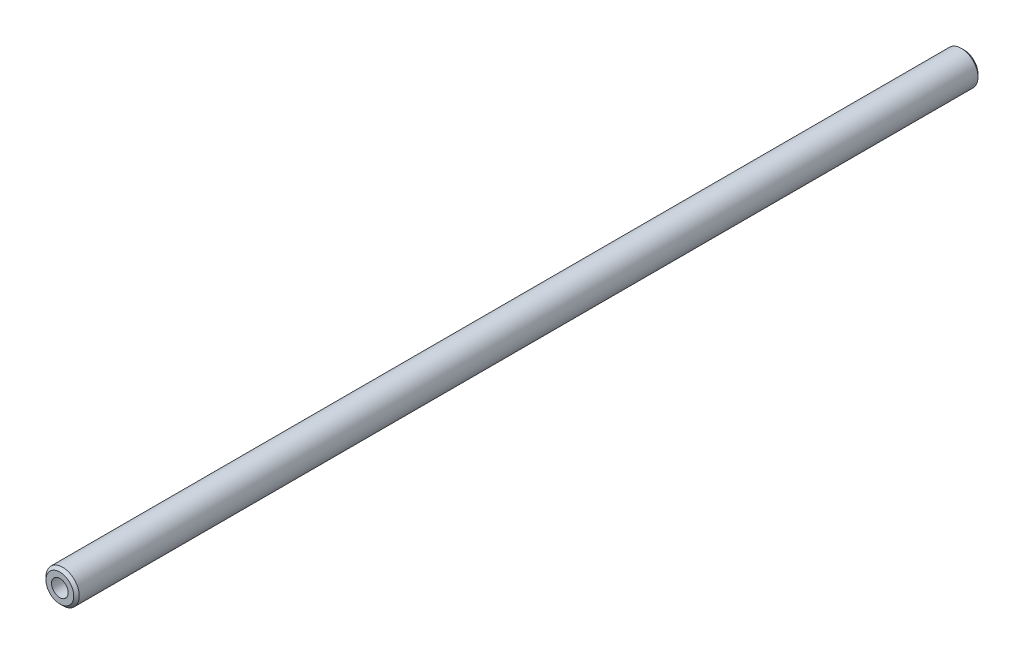
SolidWorks part; units mm, degrees
material "6061 合金"
ref_plane "前视基准面" through (0, 0, 0) normal (0, 0, 1) x (1, 0, 0)
ref_plane "上视基准面" through (0, 0, 0) normal (0, 1, 0) x (1, 0, 0)
ref_plane "右视基准面" through (0, 0, 0) normal (1, 0, 0) x (0, 0, -1)
other "Configuration Table"
sketch "草图1" plane through (0, 0, 0) normal (0, 0, 1) x (1, 0, 0)
  circle A0 centre (0, 0) radius 3
  circle A1 centre (0, 0) radius 6
  dimension "D1" = 6
  dimension "D2" = 12
extrude "凸台-拉伸1" add sketch "草图1" along normal blind 326
chamfer "倒角1" distance 1 angle 45 2 edges at (6, 0, 326) (6, 0, 0)
